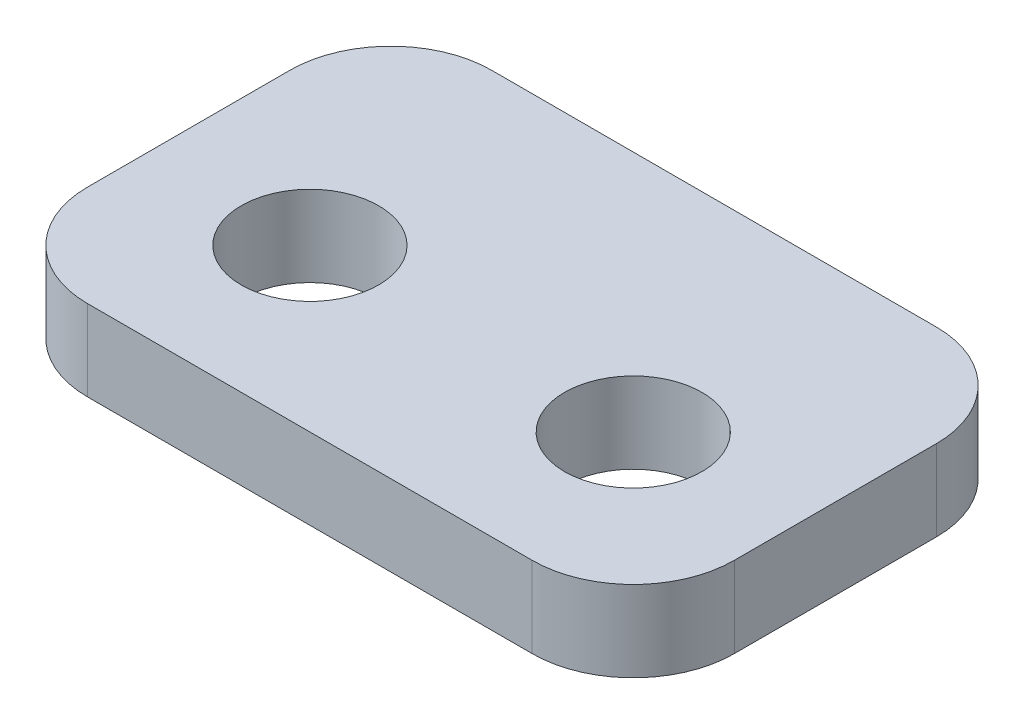
SolidWorks part; units mm, degrees
ref_plane "Plan de face" through (0, 0, 0) normal (0, 0, 1) x (1, 0, 0)
ref_plane "Plan de dessus" through (0, 0, 0) normal (0, 1, 0) x (1, 0, 0)
ref_plane "Plan de droite" through (0, 0, 0) normal (1, 0, 0) x (0, 0, -1)
sketch "Sketch1" plane through (0, 0, 0) normal (0, 1, 0) x (1, 0, 0)
  line L0 (-4, 0) -> (4, 0) construction
  line L1 (-8, -4) -> (8, -4)
  line L2 (-8, -4) -> (-8, 6)
  line L3 (-8, 6) -> (8, 6)
  line L4 (8, -4) -> (8, 6)
  circle A0 centre (-4, 0) radius 1.7
  circle A1 centre (4, 0) radius 1.7
  point P0 (0, 0)
  point P8 (0, 0)
  point P11 (0, 6)
  dimension "D3" = 3.4
  dimension "D1" = 16
  dimension "D2" = 6
  dimension "D4" = 8
  dimension "D5" = 4
extrude "Boss-Extrude1" add sketch "Sketch1" along normal blind 2
fillet "Fillet1" radius 2.5 4 edges at (-8, 1, 4) (-8, 1, -6) (8, 1, -6) (8, 1, 4)
